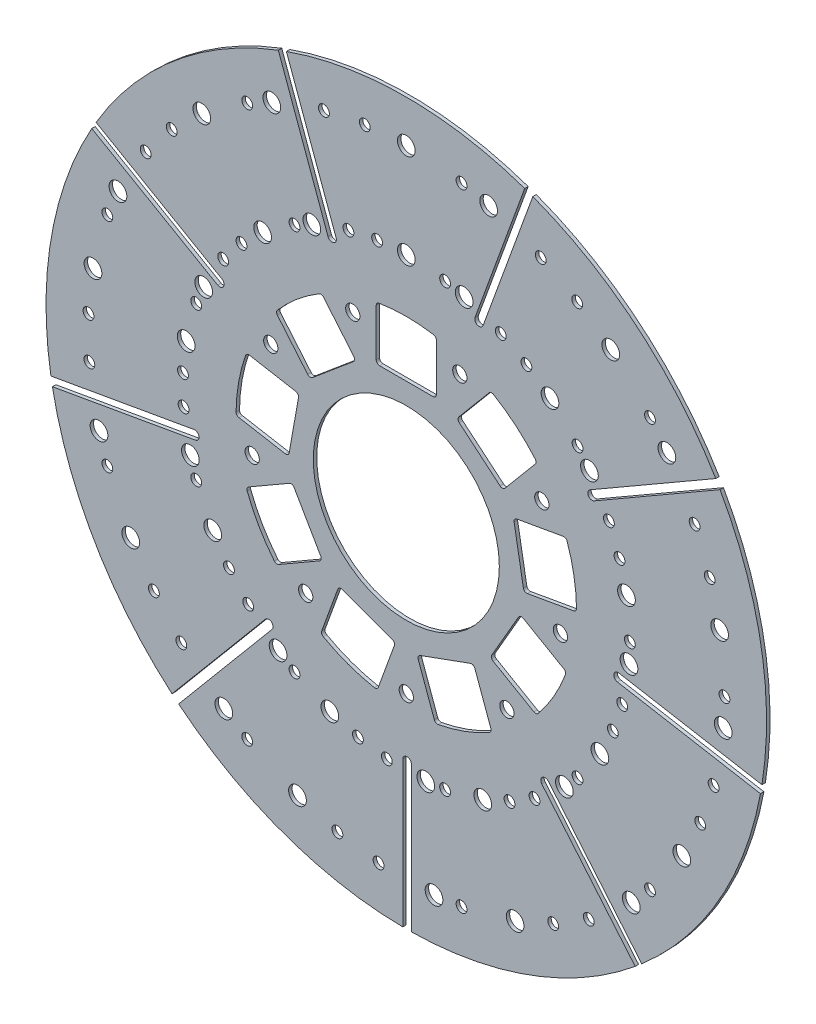
SolidWorks part; units mm, degrees
ref_plane "Plano frontal" through (0, 0, 0) normal (0, 0, 1) x (1, 0, 0)
ref_plane "Plano superior" through (0, 0, 0) normal (0, 1, 0) x (1, 0, 0)
ref_plane "Plano direito" through (0, 0, 0) normal (1, 0, 0) x (0, 0, -1)
sketch "Esboço1" plane through (0, 0, 0) normal (0, 0, 1) x (1, 0, 0)
  circle A0 centre (0, 0) radius 209.5
  circle A1 centre (0, 0) radius 54.1
  dimension "D1" = 419
  dimension "D2" = 108.2
extrude "Ressalto-extrusão1" add sketch "Esboço1" along normal blind 2
sketch "Esboço2" plane through (0, 0, 2) normal (0, 0, 1) x (1, 0, 0)
  line L0 (-132.399, -162.3869) -> (-134.3141, -160.7799)
  line L1 (-134.3141, -160.7799) -> (-136.2292, -159.173)
  line L2 (-132.399, -162.3869) -> (-78.0826, -97.6552)
  line L3 (-136.2292, -159.173) -> (-81.9128, -94.4413)
  line L4 (-205.8038, -39.2912) -> (-206.2379, -36.8291)
  line L5 (-206.2379, -36.8291) -> (-206.672, -34.3671)
  line L6 (-205.8038, -39.2912) -> (-122.5863, -24.6177)
  line L7 (-206.672, -34.3671) -> (-123.4546, -19.6936)
  line L8 (-182.9107, 102.1893) -> (-181.6607, 104.3544)
  line L9 (-181.6607, 104.3544) -> (-180.4107, 106.5195)
  line L10 (-182.9107, 102.1893) -> (-109.7305, 59.9387)
  line L11 (-180.4107, 106.5195) -> (-107.2305, 64.2689)
  line L12 (-74.4317, 195.8543) -> (-72.0825, 196.7094)
  line L13 (-72.0825, 196.7094) -> (-69.7332, 197.5644)
  line L14 (-74.4317, 195.8543) -> (-45.5306, 116.4491)
  line L15 (-69.7332, 197.5644) -> (-40.8321, 118.1592)
  line L16 (68.8747, 197.8769) -> (71.224, 197.0218)
  line L17 (71.224, 197.0218) -> (73.5732, 196.1668)
  line L18 (68.8747, 197.8769) -> (39.9736, 118.4717)
  line L19 (73.5732, 196.1668) -> (44.6721, 116.7616)
  line L20 (179.9539, 107.3107) -> (181.2039, 105.1456)
  line L21 (181.2039, 105.1456) -> (182.4539, 102.9805)
  line L22 (179.9539, 107.3107) -> (106.7737, 65.06)
  line L23 (182.4539, 102.9805) -> (109.2737, 60.7299)
  line L24 (206.8307, -33.4674) -> (206.3965, -35.9294)
  line L25 (206.3965, -35.9294) -> (205.9624, -38.3915)
  line L26 (206.8307, -33.4674) -> (123.6132, -18.7939)
  line L27 (205.9624, -38.3915) -> (122.745, -23.718)
  line L28 (136.929, -158.5857) -> (135.0139, -160.1927)
  line L29 (135.0139, -160.1927) -> (133.0988, -161.7997)
  line L30 (136.929, -158.5857) -> (82.6127, -93.854)
  line L31 (133.0988, -161.7997) -> (78.7825, -97.068)
  line L63 (2.9568, -209.5) -> (0.4568, -209.5)
  line L64 (0.4568, -209.5) -> (-2.0432, -209.5)
  line L67 (2.9568, -209.5) -> (2.9568, -124.9988)
  line L68 (-2.0432, -209.5) -> (-2.0432, -124.9988)
  arc A0 (-78.0826, -97.6552) -> (-81.9128, -94.4413) centre (-79.9977, -96.0482) ccw
  arc A1 (-122.5863, -24.6177) -> (-123.4546, -19.6936) centre (-123.0204, -22.1557) ccw
  arc A2 (-109.7305, 59.9387) -> (-107.2305, 64.2689) centre (-108.4805, 62.1038) ccw
  arc A3 (-45.5306, 116.4491) -> (-40.8321, 118.1592) centre (-43.1813, 117.3042) ccw
  arc A4 (39.9736, 118.4717) -> (44.6721, 116.7616) centre (42.3229, 117.6166) ccw
  arc A5 (106.7737, 65.06) -> (109.2737, 60.7299) centre (108.0237, 62.895) ccw
  arc A6 (123.6132, -18.7939) -> (122.745, -23.718) centre (123.1791, -21.256) ccw
  arc A7 (82.6127, -93.854) -> (78.7825, -97.068) centre (80.6976, -95.461) ccw
  arc A10 (2.9568, -124.9988) -> (-2.0432, -124.9988) centre (0.4568, -124.9988) ccw
  point P51 (0, 0)
extrude "Corte-extrusão1" cut sketch "Esboço2" against normal blind 2
sketch "Esboço3" plane through (0, 0, 2) normal (0, 0, 1) x (1, 0, 0)
  line L0 (0, 0) -> (0, 185) construction
  line L1 (0, 0) -> (32.1249, 182.1894) construction
  line L2 (0, 0) -> (47.8815, 178.6963) construction
  line L3 (0, 0) -> (-24.1473, 183.4173) construction
  line L4 (0, 0) -> (-47.8815, 178.6963) construction
  circle A0 centre (0, 0) radius 185 construction
  circle A1 centre (0, 0) radius 130 construction
  circle A2 centre (0, 185) radius 5.15
  circle A3 centre (0, 130) radius 5.15
  circle A4 centre (-24.1473, 183.4173) radius 3.15
  circle A5 centre (32.1249, 182.1894) radius 3.15
  circle A6 centre (22.5743, 128.025) radius 3.15
  circle A7 centre (-16.9684, 128.8878) radius 3.15
  circle A8 centre (-33.6465, 125.5704) radius 3.15
  circle A9 centre (33.6465, 125.5704) radius 5.15
  circle A10 centre (-47.8815, 178.6963) radius 3.15
  circle A11 centre (47.8815, 178.6963) radius 5.15
  circle A12 centre (118.9157, 141.7182) radius 5.15
  circle A13 centre (83.5624, 99.5858) radius 5.15
  circle A14 centre (99.4004, 156.0274) radius 3.15
  circle A15 centre (141.7182, 118.9157) radius 3.15
  circle A16 centre (99.5858, 83.5624) radius 3.15
  circle A17 centre (69.8489, 109.6409) radius 3.15
  circle A18 centre (54.9404, 117.82) radius 3.15
  circle A19 centre (106.4898, 74.5649) radius 5.15
  circle A20 centre (78.1844, 167.6669) radius 3.15
  circle A21 centre (151.5431, 106.1116) radius 5.15
  circle A22 centre (182.1894, 32.1249) radius 5.15
  circle A23 centre (128.025, 22.5743) radius 5.15
  circle A24 centre (176.4376, 55.6306) radius 3.15
  circle A25 centre (185, 0) radius 3.15
  circle A26 centre (130, 0) radius 3.15
  circle A27 centre (123.9832, 39.0918) radius 3.15
  circle A28 centre (117.82, 54.9404) radius 3.15
  circle A29 centre (129.5053, -11.3302) radius 5.15
  circle A30 centre (167.6669, 78.1844) radius 3.15
  circle A31 centre (184.296, -16.1238) radius 5.15
  circle A32 centre (160.2147, -92.5) radius 5.15
  circle A33 centre (112.5833, -65) radius 5.15
  circle A34 centre (170.9177, -70.7964) radius 3.15
  circle A35 centre (141.7182, -118.9157) radius 3.15
  circle A36 centre (99.5858, -83.5624) radius 3.15
  circle A37 centre (120.1043, -49.7488) radius 3.15
  circle A38 centre (125.5704, -33.6465) radius 3.15
  circle A39 centre (91.9239, -91.9239) radius 5.15
  circle A40 centre (178.6963, -47.8815) radius 3.15
  circle A41 centre (130.8148, -130.8148) radius 5.15
  circle A42 centre (63.2737, -173.8431) radius 5.15
  circle A43 centre (44.4626, -122.16) radius 5.15
  circle A44 centre (85.4235, -164.097) radius 3.15
  circle A45 centre (32.1249, -182.1894) radius 3.15
  circle A46 centre (22.5743, -128.025) radius 3.15
  circle A47 centre (60.0273, -115.3114) radius 3.15
  circle A48 centre (74.5649, -106.4898) radius 3.15
  circle A49 centre (11.3302, -129.5053) radius 5.15
  circle A50 centre (106.1116, -151.5431) radius 3.15
  circle A51 centre (16.1238, -184.296) radius 5.15
  circle A52 centre (-63.2737, -173.8431) radius 5.15
  circle A53 centre (-44.4626, -122.16) radius 5.15
  circle A54 centre (-40.0413, -180.6148) radius 3.15
  circle A55 centre (-92.5, -160.2147) radius 3.15
  circle A56 centre (-65, -112.5833) radius 3.15
  circle A57 centre (-28.1371, -126.9185) radius 3.15
  circle A58 centre (-11.3302, -129.5053) radius 3.15
  circle A59 centre (-74.5649, -106.4898) radius 5.15
  circle A60 centre (-16.1238, -184.296) radius 3.15
  circle A61 centre (-106.1116, -151.5431) radius 5.15
  circle A62 centre (-160.2147, -92.5) radius 5.15
  circle A63 centre (-112.5833, -65) radius 5.15
  circle A64 centre (-146.7704, -112.6209) radius 3.15
  circle A65 centre (-173.8431, -63.2737) radius 3.15
  circle A66 centre (-122.16, -44.4626) radius 3.15
  circle A67 centre (-103.1359, -79.139) radius 3.15
  circle A68 centre (-91.9239, -91.9239) radius 3.15
  circle A69 centre (-125.5704, -33.6465) radius 5.15
  circle A70 centre (-130.8148, -130.8148) radius 3.15
  circle A71 centre (-178.6963, -47.8815) radius 5.15
  circle A72 centre (-182.1894, 32.1249) radius 5.15
  circle A73 centre (-128.025, 22.5743) radius 5.15
  circle A74 centre (-184.8239, 8.0696) radius 3.15
  circle A75 centre (-173.8431, 63.2737) radius 3.15
  circle A76 centre (-122.16, 44.4626) radius 3.15
  circle A77 centre (-129.8763, 5.6705) radius 3.15
  circle A78 centre (-129.5053, -11.3302) radius 3.15
  circle A79 centre (-117.82, 54.9404) radius 5.15
  circle A80 centre (-184.296, -16.1238) radius 3.15
  circle A81 centre (-167.6669, 78.1844) radius 5.15
  circle A82 centre (-118.9157, 141.7182) radius 5.15
  circle A83 centre (-83.5624, 99.5858) radius 5.15
  circle A84 centre (-136.3963, 124.9842) radius 3.15
  circle A85 centre (-92.5, 160.2147) radius 3.15
  circle A86 centre (-65, 112.5833) radius 3.15
  circle A87 centre (-95.8461, 87.8267) radius 3.15
  circle A88 centre (-106.4898, 74.5649) radius 3.15
  circle A89 centre (-54.9404, 117.82) radius 5.15
  circle A90 centre (-151.5431, 106.1116) radius 3.15
  circle A91 centre (-78.1844, 167.6669) radius 5.15
  point P189 (0, 0)
  dimension "D1" = 370
  dimension "D2" = 260
  dimension "D3" = 10.3
  dimension "D4" = 10.3
  dimension "D9" = 6.3
  dimension "D5" = 10
  dimension "D6" = 5
  dimension "D7" = 7.5
  dimension "D8" = 7.5
extrude "Corte-extrusão2" cut sketch "Esboço3" against normal blind 2
sketch "Esboço4" plane through (0, 0, 2) normal (0, 0, 1) x (1, 0, 0)
  line L0 (0, 99) -> (0, 0) construction
  line L1 (29.2753, 62.1141) -> (56.0869, 39.6166)
  line L2 (-17.5, 66.4) -> (17.5, 66.4)
  line L3 (-17.5, 66.4) -> (-17.5, 97.441)
  line L4 (17.5, 66.4) -> (17.5, 97.441)
  line L5 (29.2753, 62.1141) -> (49.2281, 85.8929)
  line L6 (56.0869, 39.6166) -> (76.0397, 63.3954)
  line L7 (62.3524, 28.7644) -> (68.4301, -5.7039)
  line L8 (62.3524, 28.7644) -> (92.9218, 34.1546)
  line L9 (68.4301, -5.7039) -> (98.9995, -0.3137)
  line L10 (66.2541, -18.0446) -> (48.7541, -48.3554)
  line L11 (66.2541, -18.0446) -> (93.1364, -33.5651)
  line L12 (48.7541, -48.3554) -> (75.6364, -63.8759)
  line L13 (39.1548, -56.4102) -> (6.2655, -68.3809)
  line L14 (39.1548, -56.4102) -> (49.7714, -85.5792)
  line L15 (6.2655, -68.3809) -> (16.8822, -97.5499)
  line L16 (-6.2655, -68.3809) -> (-39.1548, -56.4102)
  line L17 (-6.2655, -68.3809) -> (-16.8822, -97.5499)
  line L18 (-39.1548, -56.4102) -> (-49.7714, -85.5792)
  line L19 (-48.7541, -48.3554) -> (-66.2541, -18.0446)
  line L20 (-48.7541, -48.3554) -> (-75.6364, -63.8759)
  line L21 (-66.2541, -18.0446) -> (-93.1364, -33.5651)
  line L22 (-68.4301, -5.7039) -> (-62.3524, 28.7644)
  line L23 (-68.4301, -5.7039) -> (-98.9995, -0.3137)
  line L24 (-62.3524, 28.7644) -> (-92.9218, 34.1546)
  line L25 (-56.0869, 39.6166) -> (-29.2753, 62.1141)
  line L26 (-56.0869, 39.6166) -> (-76.0397, 63.3954)
  line L27 (-29.2753, 62.1141) -> (-49.2281, 85.8929)
  arc A0 (49.2281, 85.8929) -> (76.0397, 63.3954) centre (0, 0) cw
  arc A1 (-17.5, 97.441) -> (17.5, 97.441) centre (0, 0) cw
  arc A2 (92.9218, 34.1546) -> (98.9995, -0.3137) centre (0, 0) cw
  arc A3 (93.1364, -33.5651) -> (75.6364, -63.8759) centre (0, 0) cw
  arc A4 (49.7714, -85.5792) -> (16.8822, -97.5499) centre (0, 0) cw
  arc A5 (-16.8822, -97.5499) -> (-49.7714, -85.5792) centre (0, 0) cw
  arc A6 (-75.6364, -63.8759) -> (-93.1364, -33.5651) centre (0, 0) cw
  arc A7 (-98.9995, -0.3137) -> (-92.9218, 34.1546) centre (0, 0) cw
  arc A8 (-76.0397, 63.3954) -> (-49.2281, 85.8929) centre (0, 0) cw
  point P42 (0, 0)
extrude "Corte-extrusão3" cut sketch "Esboço4" against normal blind 2
sketch "Esboço5" plane through (0, 0, 2) normal (0, 0, 1) x (1, 0, 0)
  circle A0 centre (0, 0) radius 91 construction
  circle A2 centre (31.1238, 85.512) radius 4.15
  circle A4 centre (78.8083, 45.5) radius 4.15
  circle A6 centre (89.6175, -15.802) radius 4.15
  circle A8 centre (58.4937, -69.71) radius 4.15
  circle A10 centre (0, -91) radius 4.15
  circle A12 centre (-58.4937, -69.71) radius 4.15
  circle A14 centre (-89.6175, -15.802) radius 4.15
  circle A16 centre (-78.8083, 45.5) radius 4.15
  circle A18 centre (-31.1238, 85.512) radius 4.15
  point P41 (0, 0)
  dimension "D1" = 182
extrude "Corte-extrusão4" cut sketch "Esboço5" against normal blind 2
fillet "Filete1" radius 2 36 edges at (-48.7541, -48.3554, 1) (-75.6364, -63.8759, 1) (-93.1364, -33.5651, 1) (-66.2541, -18.0446, 1) (-16.8822, -97.5499, 1) (-49.7714, -85.5792, 1) (-39.1548, -56.4102, 1) (-6.2655, -68.3809, 1) (49.7714, -85.5792, 1) (16.8822, -97.5499, 1) (6.2655, -68.3809, 1) (39.1548, -56.4102, 1) (93.1364, -33.5651, 1) (75.6364, -63.8759, 1) (48.7541, -48.3554, 1) (66.2541, -18.0446, 1) (68.4301, -5.7039, 1) (98.9995, -0.3137, 1) (62.3524, 28.7644, 1) (92.9218, 34.1546, 1) (56.0869, 39.6166, 1) (76.0397, 63.3954, 1) (29.2753, 62.1141, 1) (49.2281, 85.8929, 1) (-17.5, 66.4, 1) (17.5, 66.4, 1) (17.5, 97.441, 1) (-17.5, 97.441, 1) (-76.0397, 63.3954, 1) (-29.2753, 62.1141, 1) (-49.2281, 85.8929, 1) (-56.0869, 39.6166, 1) (-68.4301, -5.7039, 1) (-98.9995, -0.3137, 1) (-92.9218, 34.1546, 1) (-62.3524, 28.7644, 1)
